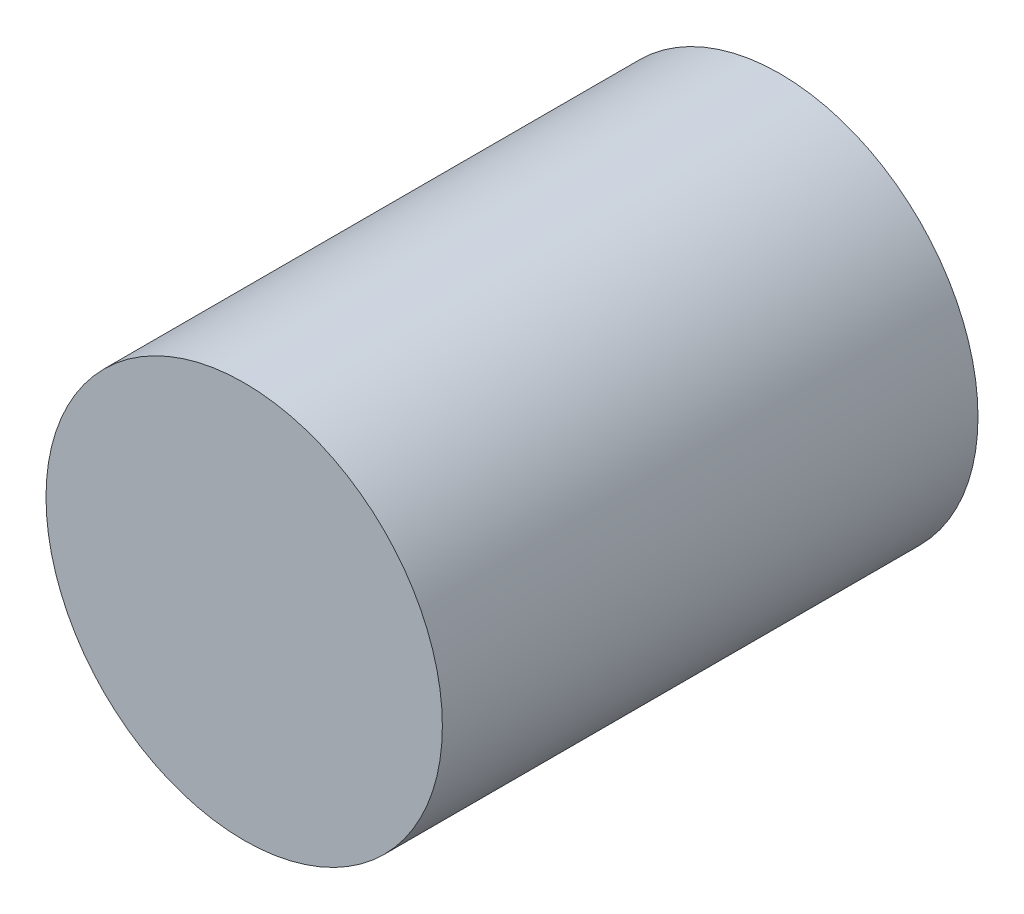
SolidWorks part; units mm, degrees
ref_plane "Front" through (0, 0, 0) normal (0, 0, 1) x (1, 0, 0)
ref_plane "Top" through (0, 0, 0) normal (0, 1, 0) x (1, 0, 0)
ref_plane "Right" through (0, 0, 0) normal (1, 0, 0) x (0, 0, -1)
sketch "Sketch1" plane through (0, 0, 0) normal (0, 0, 1) x (1, 0, 0)
  circle A0 centre (0, 0) radius 4.699
  dimension "D1" = 9.398
extrude "Base-Extrude" add sketch "Sketch1" along normal blind 12.7
